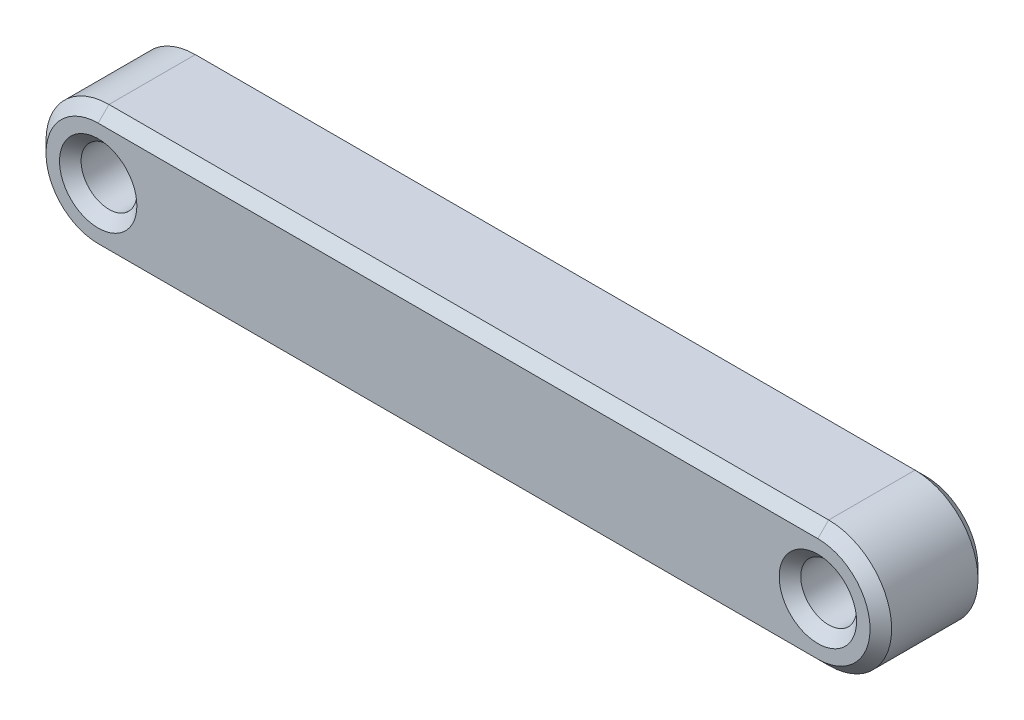
SolidWorks part; units mm, degrees
ref_plane "前视基准面" through (0, 0, 0) normal (0, 0, 1) x (1, 0, 0)
ref_plane "上视基准面" through (0, 0, 0) normal (0, 1, 0) x (1, 0, 0)
ref_plane "右视基准面" through (0, 0, 0) normal (1, 0, 0) x (0, 0, -1)
sketch "草图1" plane through (0, 0, 0) normal (0, 0, 1) x (1, 0, 0)
  line L0 (0, 0) -> (40, 0) construction
  line L1 (0, 3.5) -> (40, 3.5)
  line L2 (0, -3.5) -> (40, -3.5)
  circle A0 centre (0, 0) radius 1.55
  circle A1 centre (0, 0) radius 3.5
  circle A2 centre (40, 0) radius 1.55
  circle A3 centre (40, 0) radius 3.5
  dimension "D1" = 3.1
  dimension "D2" = 7
  dimension "D3" = 3.1
  dimension "D4" = 7
  dimension "D5" = 40
extrude "凸台-拉伸1" add sketch "草图1" along normal blind 6
chamfer "倒角1" distance 0.6 angle 45 12 edges at (1.55, 0, 0) (41.55, 0, 0) (43.5, 0, 0) (20, 3.5, 0) (-3.5, 0, 0) (20, -3.5, 0) (1.55, 0, 6) (41.55, 0, 6) (-3.5, 0, 6) (20, 3.5, 6) (43.5, 0, 6) (20, -3.5, 6)
